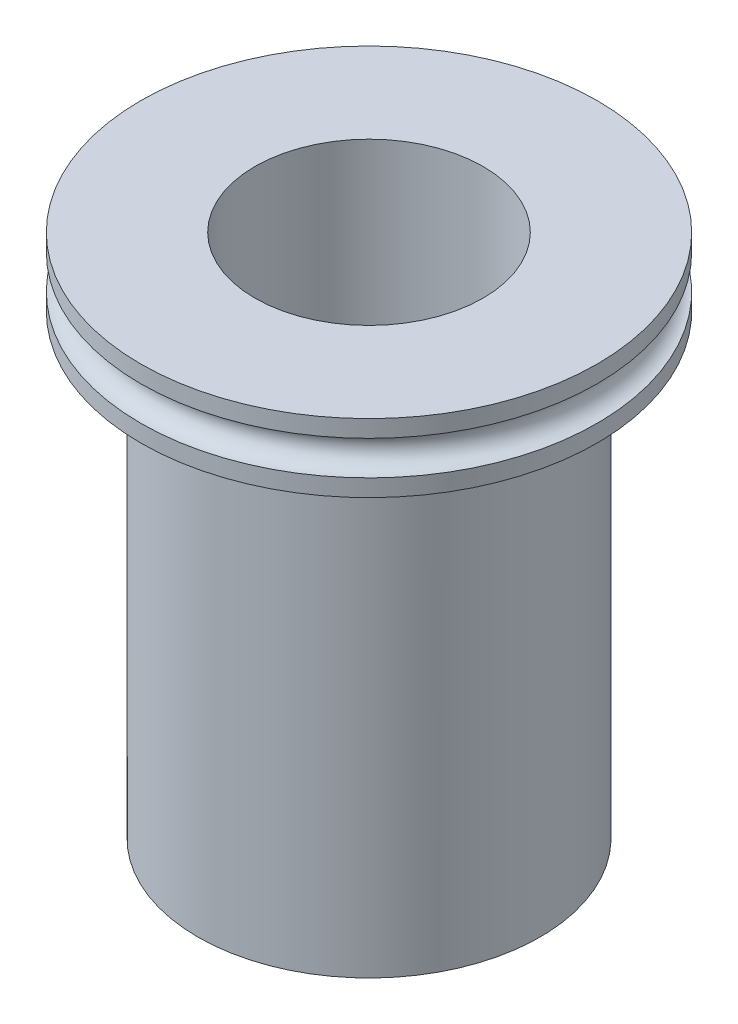
SolidWorks part; units mm, degrees
ref_plane "Alzado" through (0, 0, 0) normal (0, 0, 1) x (1, 0, 0)
ref_plane "Planta" through (0, 0, 0) normal (0, 1, 0) x (1, 0, 0)
ref_plane "Vista lateral" through (0, 0, 0) normal (1, 0, 0) x (0, 0, -1)
sketch "Croquis1" plane through (0, 0, 0) normal (0, 1, 0) x (1, 0, 0)
  circle A0 centre (0, 0) radius 10
  dimension "D1" = 20
extrude "Saliente-Extruir1" add sketch "Croquis1" along normal blind 3
ref_axis "Eje1" through (0, 3, 0) along (0, -1, 0)
sketch "Croquis2" plane through (0, 0, 0) normal (1, 0, 0) x (0, 0, -1)
  line L0 (10, 0) -> (10, 3) construction
  circle A0 centre (10, 1.5) radius 0.75
  dimension "D1" = 1.5
revolve "Cortar-Revolución1" cut sketch "Croquis2" angle 360 about axis through (0, 3, 0) along (0, -1, 0)
sketch "Croquis4" plane through (0, 0, 0) normal (0, -1, 0) x (1, 0, 0)
  circle A0 centre (0, 0) radius 7.5
  dimension "D1" = 15
extrude "Saliente-Extruir2" add sketch "Croquis4" along normal blind 20
sketch "Croquis3" plane through (0, 3, 0) normal (0, 1, 0) x (1, 0, 0)
  circle A0 centre (0, 0) radius 5
  dimension "D1" = 10
extrude "Cortar-Extruir1" cut sketch "Croquis3" against normal through all
